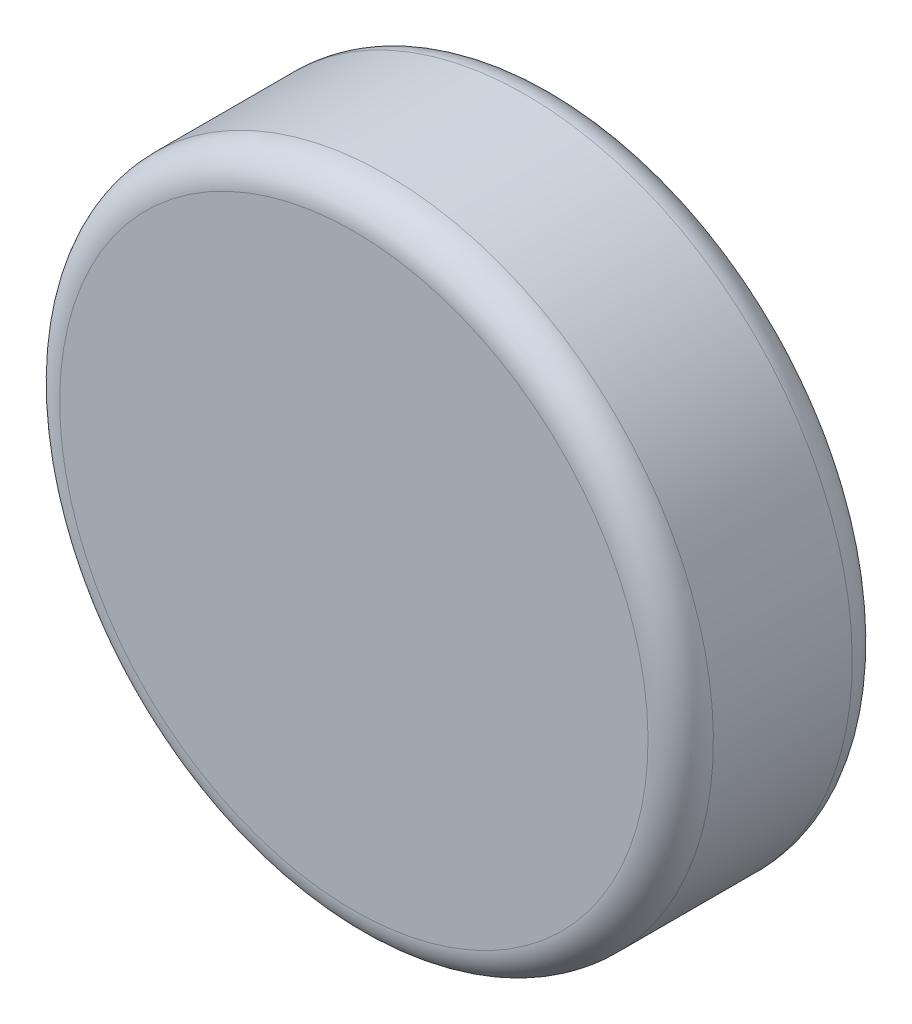
SolidWorks part; units mm, degrees
ref_plane "Front Plane" through (0, 0, 0) normal (0, 0, 1) x (1, 0, 0)
ref_plane "Top Plane" through (0, 0, 0) normal (0, 1, 0) x (1, 0, 0)
ref_plane "Right Plane" through (0, 0, 0) normal (1, 0, 0) x (0, 0, -1)
sketch "Sketch1" plane through (0, 0, 16.895) normal (0, 0, -1) x (-1, 0, 0)
  circle A0 centre (4.95, -15.4) radius 4 construction
  circle A1 centre (4.95, -15.4) radius 4
extrude "Boss-Extrude1" add sketch "Sketch1" along normal blind 2.5
fillet "Fillet1" radius 0.4 2 edges at (-4.95, -11.4, 16.895) (-4.95, -11.4, 14.395)
